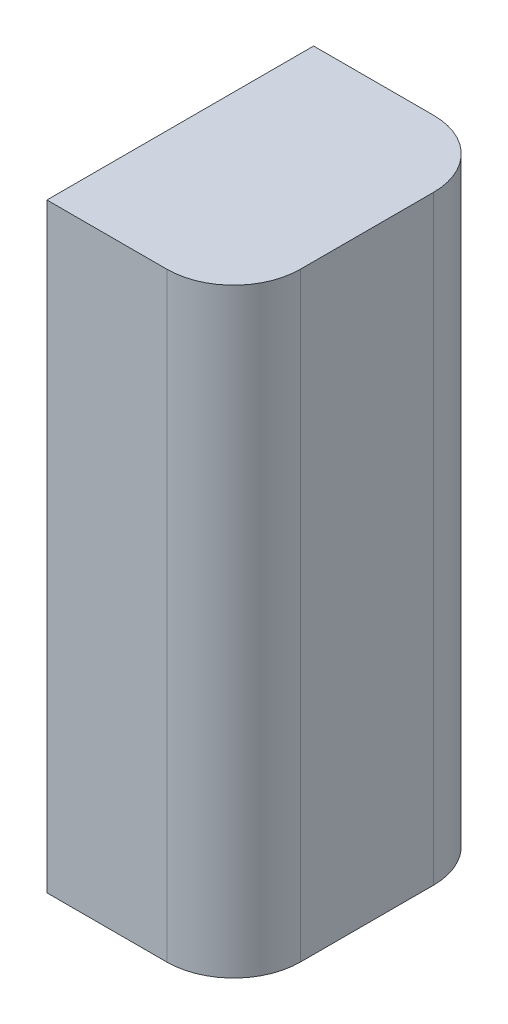
SolidWorks part; units mm, degrees
ref_plane "Front Plane" through (0, 0, 0) normal (0, 0, 1) x (1, 0, 0)
ref_plane "Top Plane" through (0, 0, 0) normal (0, 1, 0) x (1, 0, 0)
ref_plane "Right Plane" through (0, 0, 0) normal (1, 0, 0) x (0, 0, -1)
sketch "Sketch1" plane through (0, 0, 0) normal (0, 1, 0) x (1, 0, 0)
  line L1 (0, 0) -> (57.15, 0)
  line L2 (0, 0) -> (0, 127)
  line L3 (0, 127) -> (57.15, 127)
  line L4 (88.9, 31.75) -> (88.9, 95.25)
  arc A0 (57.15, 0) -> (88.9, 31.75) centre (57.15, 31.75) ccw
  arc A1 (57.15, 127) -> (88.9, 95.25) centre (57.15, 95.25) cw
  point P7 (88.9, 0)
  dimension "D3" = 31.75
  dimension "D1" = 127
  dimension "D2" = 88.9
extrude "Boss-Extrude1" add sketch "Sketch1" along normal blind 285.75
